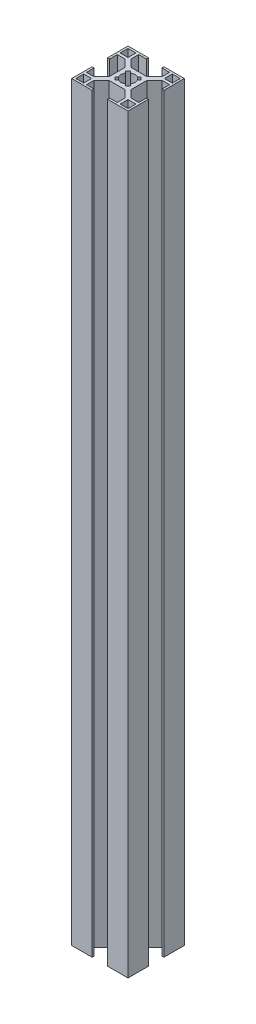
SolidWorks part; units mm, degrees
material "3.0255 (EN-AW 1350A)"
ref_plane "Alzado" through (0, 0, 0) normal (0, 0, 1) x (1, 0, 0)
ref_plane "Planta" through (0, 0, 0) normal (0, 1, 0) x (1, 0, 0)
ref_plane "Vista lateral" through (0, 0, 0) normal (1, 0, 0) x (0, 0, -1)
sketch "Croquis2" plane through (0, 0, 0) normal (0, 1, 0) x (1, 0, 0)
  line L0 (-12.6732, 23.1711) -> (-8.4732, 23.1711)
  line L1 (-37.3732, 24.2711) -> (-26.4982, 24.2711)
  line L2 (-37.3732, 24.2711) -> (-37.3732, 13.3961)
  line L3 (-37.3732, -5.7289) -> (-26.4982, -5.7289)
  line L4 (-7.3732, 24.2711) -> (-7.3732, 13.3961)
  line L5 (-30.5732, -4.6289) -> (-26.4982, -4.6289)
  line L6 (-30.5732, 23.1711) -> (-26.4982, 23.1711)
  line L7 (-36.2732, 5.1461) -> (-37.3732, 5.1461)
  line L8 (-8.4732, 23.1711) -> (-8.4732, 18.9711)
  line L9 (-36.2732, -4.6289) -> (-32.0732, -4.6289)
  line L10 (-36.2732, 23.1711) -> (-36.2732, 18.9711)
  line L11 (-36.2732, 23.1711) -> (-32.0732, 23.1711)
  line L12 (-32.0732, -0.4289) -> (-36.2732, -0.4289)
  line L15 (-8.4732, 18.9711) -> (-12.6732, 18.9711)
  line L16 (-12.6732, 23.1711) -> (-12.6732, 18.9711)
  line L17 (-32.0732, -0.4289) -> (-32.0732, -4.6289)
  line L19 (-36.2732, -0.4289) -> (-36.2732, -4.6289)
  line L21 (-32.0732, 23.1711) -> (-32.0732, 18.9711)
  line L22 (-32.0732, 18.9711) -> (-36.2732, 18.9711)
  line L24 (-8.4732, -0.4289) -> (-12.6732, -0.4289)
  line L25 (-8.4732, -0.4289) -> (-8.4732, -4.6289)
  line L26 (-8.4732, -4.6289) -> (-12.6732, -4.6289)
  line L27 (-12.6732, -0.4289) -> (-12.6732, -4.6289)
  line L28 (-26.5862, 3.3611) -> (-18.1603, 3.3611)
  line L29 (-16.4632, 13.4841) -> (-16.4632, 5.0582)
  line L30 (-26.5862, 15.1811) -> (-18.1603, 15.1811)
  line L31 (-28.2832, 13.4841) -> (-28.2832, 5.0582)
  line L32 (-28.2832, 15.1811) -> (-16.4632, 15.1811) construction
  line L33 (-28.2832, 3.3611) -> (-16.4632, 3.3611) construction
  line L34 (-7.3732, 5.1461) -> (-8.4732, 5.1461)
  line L35 (-7.3732, 13.3961) -> (-8.4732, 13.3961)
  line L36 (-26.4982, 24.2711) -> (-26.4982, 23.1711)
  line L37 (-18.2482, 24.2711) -> (-18.2482, 23.1711)
  line L38 (-36.2732, 13.3961) -> (-37.3732, 13.3961)
  line L39 (-19.1655, 11.0646) -> (-18.2482, 11.9819)
  line L40 (-36.2732, 5.1461) -> (-36.2732, 1.0711)
  line L41 (-36.2732, 23.1711) -> (-36.2732, -4.6289) construction
  line L42 (-37.3732, 5.1461) -> (-37.3732, -5.7289)
  line L43 (-37.3732, 24.2711) -> (-37.3732, -5.7289) construction
  line L44 (-18.2482, -4.6289) -> (-18.2482, -5.7289)
  line L46 (-8.4732, 5.1461) -> (-8.4732, 1.0711)
  line L47 (-8.4732, 23.1711) -> (-8.4732, -4.6289) construction
  line L48 (-7.3732, 5.1461) -> (-7.3732, -5.7289)
  line L49 (-7.3732, 24.2711) -> (-7.3732, -5.7289) construction
  line L51 (-25.084, 5.1461) -> (-24.1667, 6.0634)
  line L52 (-18.2482, -4.6289) -> (-14.1732, -4.6289)
  line L53 (-36.2732, -4.6289) -> (-8.4732, -4.6289) construction
  line L54 (-18.2482, -5.7289) -> (-7.3732, -5.7289)
  line L55 (-37.3732, -5.7289) -> (-7.3732, -5.7289) construction
  line L56 (-16.4632, 15.1811) -> (-16.4632, 3.3611) construction
  line L57 (-26.4982, 11.9819) -> (-25.5809, 11.0646)
  line L58 (-18.2482, 23.1711) -> (-14.1732, 23.1711)
  line L59 (-36.2732, 23.1711) -> (-8.4732, 23.1711) construction
  line L60 (-18.2482, 24.2711) -> (-7.3732, 24.2711)
  line L61 (-37.3732, 24.2711) -> (-7.3732, 24.2711) construction
  line L62 (-32.2703, 1.0711) -> (-36.2732, 1.0711)
  line L63 (-30.5732, 1.0711) -> (-37.7732, 1.0711) construction
  line L64 (-30.5732, 1.0711) -> (-30.5732, -6.1289) construction
  line L65 (-30.5732, -0.6259) -> (-30.5732, -4.6289)
  line L66 (-8.4732, 1.0711) -> (-12.4762, 1.0711)
  line L67 (-14.1732, -0.6259) -> (-14.1732, -4.6289)
  line L68 (-6.9732, 1.0711) -> (-6.9732, -6.1289) construction
  line L69 (-30.5732, -0.6259) -> (-26.5862, 3.3611)
  line L70 (-6.9732, 17.4711) -> (-14.1732, 17.4711) construction
  line L71 (-8.4732, 17.4711) -> (-12.4762, 17.4711)
  line L72 (-14.1732, 23.1711) -> (-14.1732, 19.1682)
  line L73 (-8.4732, 17.4711) -> (-8.4732, 13.3961)
  line L74 (-32.2703, 17.4711) -> (-36.2732, 17.4711)
  line L75 (-30.5732, 24.6711) -> (-30.5732, 17.4711) construction
  line L76 (-16.4632, 13.4841) -> (-12.4762, 17.4711)
  line L77 (-30.5732, 23.1711) -> (-30.5732, 19.1682)
  line L78 (-30.5732, -6.1289) -> (-37.7732, -6.1289) construction
  line L79 (-37.7732, 1.0711) -> (-37.7732, -6.1289) construction
  line L80 (-26.4982, -4.6289) -> (-26.4982, -5.7289)
  line L81 (-30.5732, 19.1682) -> (-26.5862, 15.1811)
  line L83 (-18.1603, 3.3611) -> (-14.1732, -0.6259)
  line L84 (-30.5732, 17.4711) -> (-37.7732, 17.4711) construction
  line L85 (-37.7732, 24.6711) -> (-37.7732, 17.4711) construction
  line L86 (-30.5732, 24.6711) -> (-37.7732, 24.6711) construction
  line L87 (-36.2732, 17.4711) -> (-36.2732, 13.3961)
  line L88 (-32.2703, 1.0711) -> (-28.2832, 5.0582)
  line L90 (-6.9732, -6.1289) -> (-14.1732, -6.1289) construction
  line L91 (-14.1732, 1.0711) -> (-14.1732, -6.1289) construction
  line L92 (-6.9732, 1.0711) -> (-14.1732, 1.0711) construction
  line L94 (-25.084, 13.3961) -> (-24.1667, 12.4788)
  line L95 (-19.1655, 7.4777) -> (-18.2482, 6.5603)
  line L96 (-20.5798, 6.0634) -> (-19.6624, 5.1461)
  line L97 (-14.1732, 24.6711) -> (-14.1732, 17.4711) construction
  line L98 (-6.9732, 24.6711) -> (-14.1732, 24.6711) construction
  line L99 (-6.9732, 24.6711) -> (-6.9732, 17.4711) construction
  line L100 (-16.4632, 5.0582) -> (-12.4762, 1.0711)
  line L101 (-26.4982, 6.5603) -> (-25.5809, 7.4777)
  line L104 (-28.2832, 15.1811) -> (-28.2832, 3.3611) construction
  line L105 (-18.1603, 15.1811) -> (-14.1732, 19.1682)
  line L106 (-32.2703, 17.4711) -> (-28.2832, 13.4841)
  line L111 (-20.5798, 12.4788) -> (-19.6624, 13.3961)
  line L114 (-26.4982, 6.5603) -> (-25.084, 5.1461)
  line L115 (-19.6624, 5.1461) -> (-18.2482, 6.5603)
  line L116 (-19.6624, 13.3961) -> (-18.2482, 11.9819)
  line L117 (-25.084, 13.3961) -> (-26.4982, 11.9819)
  line L119 (-32.0732, 23.1711) -> (-36.2732, 23.1711) construction
  line L120 (-8.4732, 23.1711) -> (-12.6732, 23.1711) construction
  line L121 (-32.0732, -4.6289) -> (-36.2732, -4.6289) construction
  line L122 (-8.4732, 23.1711) -> (-8.4732, 18.9711) construction
  line L123 (-36.2732, 23.1711) -> (-36.2732, 18.9711) construction
  arc A0 (-25.5809, 11.0646) -> (-25.5809, 7.4777) centre (-22.3732, 9.2711) ccw
  arc A1 (-20.5798, 12.4788) -> (-24.1667, 12.4788) centre (-22.3732, 9.2711) ccw
  arc A2 (-19.1655, 7.4777) -> (-19.1655, 11.0646) centre (-22.3732, 9.2711) ccw
  arc A3 (-24.1667, 6.0634) -> (-20.5798, 6.0634) centre (-22.3732, 9.2711) ccw
  dimension "D1" = 30
  dimension "D2" = 30
  dimension "D5" = 1.5
extrude "Saliente-Extruir1" add sketch "Croquis2" along normal blind 400
